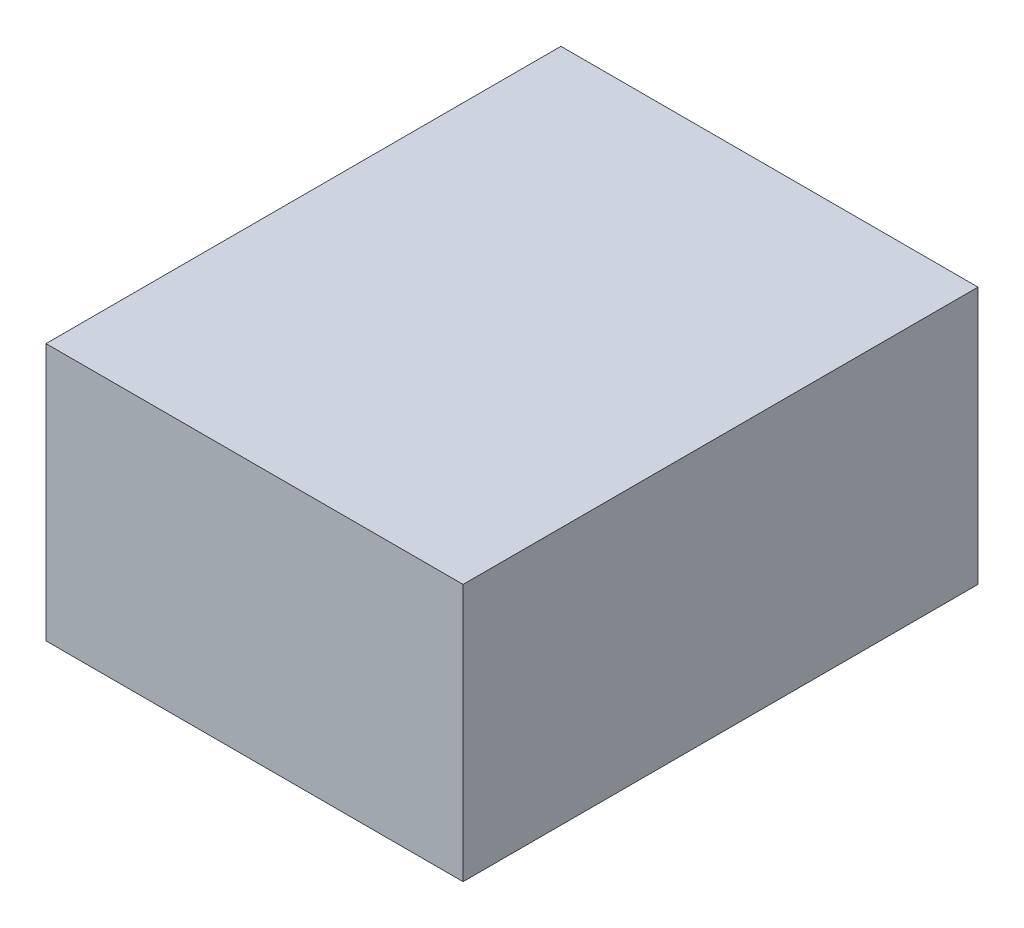
SolidWorks part; units mm, degrees
ref_plane "Front Plane" through (0, 0, 0) normal (0, 0, 1) x (1, 0, 0)
ref_plane "Top Plane" through (0, 0, 0) normal (0, 1, 0) x (1, 0, 0)
ref_plane "Right Plane" through (0, 0, 0) normal (1, 0, 0) x (0, 0, -1)
sketch "Sketch1" plane through (0, 0, 0) normal (0, 1, 0) x (1, 0, 0)
  line L1 (0, 0) -> (16.2, 0)
  line L2 (0, 0) -> (0, 20)
  line L3 (0, 20) -> (16.2, 20)
  line L4 (16.2, 0) -> (16.2, 20)
extrude "Boss-Extrude1" add sketch "Sketch1" against normal blind 10
